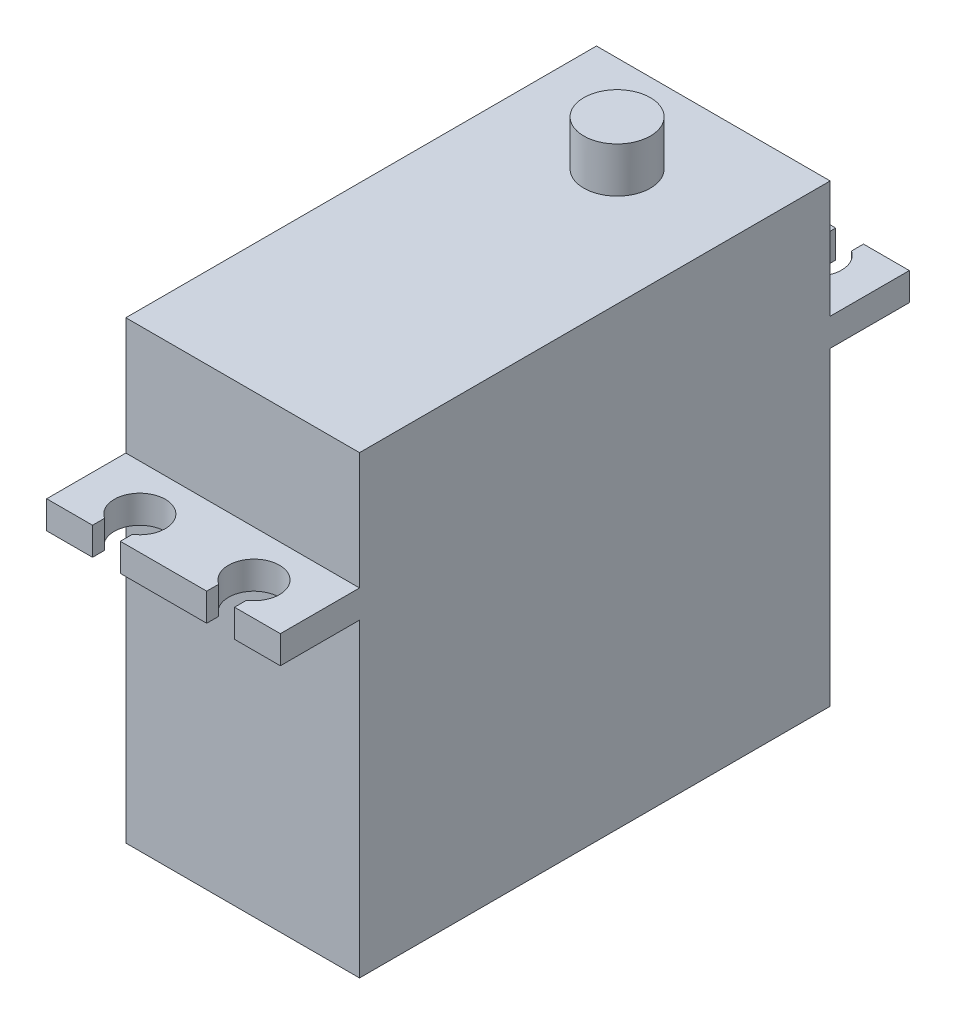
SolidWorks part; units mm, degrees
ref_plane "Front Plane" through (0, 0, 0) normal (0, 0, 1) x (1, 0, 0)
ref_plane "Top Plane" through (0, 0, 0) normal (0, 1, 0) x (1, 0, 0)
ref_plane "Right Plane" through (0, 0, 0) normal (1, 0, 0) x (0, 0, -1)
sketch "Sketch1" plane through (0, 0, 0) normal (1, 0, 0) x (0, 0, -1)
  line L1 (20.3, 0) -> (-20.3, 0)
  line L2 (20.3, 0) -> (20.3, 39.25)
  line L3 (20.3, 39.25) -> (-20.3, 39.25)
  line L4 (-20.3, 0) -> (-20.3, 39.25)
  dimension "D1" = 39.25
  dimension "D2" = 40.6
extrude "Boss-Extrude1" add sketch "Sketch1" along normal mid plane 20.16
ref_plane "Plane1" through (0, 29.14, 0) normal (0, 1, 0) x (1, 0, 0)
sketch "Sketch2" plane through (0, 29.14, 0) normal (0, 1, 0) x (1, 0, 0)
  line L0 (10.08, 20.3) -> (10.08, -20.3) construction
  line L1 (-10.08, -20.3) -> (10.08, -20.3)
  line L2 (-10.08, -20.3) -> (-10.08, -27.13)
  line L3 (-10.08, -27.13) -> (-6.1246, -27.13)
  line L4 (10.08, -20.3) -> (10.08, -27.13)
  line L5 (0, -47.43) -> (0, -20.3) construction
  line L6 (10.08, 0) -> (-10.08, 0) construction
  line L7 (-10.08, 20.3) -> (-10.08, -20.3) construction
  line L8 (6.1246, -27.13) -> (6.1246, -26.0942)
  line L9 (3.7254, -27.13) -> (3.7254, -26.0942)
  line L10 (-3.7254, -27.13) -> (-3.7254, -26.0942)
  line L11 (-6.1246, -27.13) -> (-6.1246, -26.0942)
  line L12 (6.1246, -27.13) -> (10.08, -27.13)
  line L13 (-3.7254, -27.13) -> (3.7254, -27.13)
  arc A0 (6.1246, -26.0942) -> (3.7254, -26.0942) centre (4.925, -24.25) ccw
  arc A1 (-6.1246, -26.0942) -> (-3.7254, -26.0942) centre (-4.925, -24.25) cw
  point P13 (2.725, -24.25)
  point P14 (-2.725, -24.25)
  point P19 (4.925, -22.05)
  dimension "D2" = 4.4
  dimension "D1" = 6.83
  dimension "D3" = 5.45
  dimension "D4" = 22.05
  dimension "D5" = 2.3992
extrude "Boss-Extrude2" add sketch "Sketch2" against normal blind 2.4
mirror "Mirror1" about plane through (0, 0, 0) normal (0, 0, 1) of "Boss-Extrude2"
sketch "Sketch3" plane through (0, 0, -20.3) normal (0, 0, -1) x (-1, 0, 0)
  line L0 (0, 3.4743) -> (0, 0) construction
  line L1 (3.2, 7.5743) -> (-3.2, 7.5743)
  line L2 (3.2, 7.5743) -> (3.2, 3.4743)
  line L3 (3.2, 3.4743) -> (-3.2, 3.4743)
  line L4 (-3.2, 7.5743) -> (-3.2, 3.4743)
  dimension "D1" = 4.1
  dimension "D2" = 6.4
extrude "Boss-Extrude3" add sketch "Sketch3" along normal blind 6
sketch "Sketch4" plane through (0, 39.25, 0) normal (0, 1, 0) x (1, 0, 0)
  line L0 (10.08, -20.3) -> (-10.08, -20.3) construction
  circle A0 centre (0, 12) radius 2.87
  dimension "D1" = 5.74
  dimension "D2" = 32.3
extrude "Boss-Extrude4" add sketch "Sketch4" along normal blind 3.9
